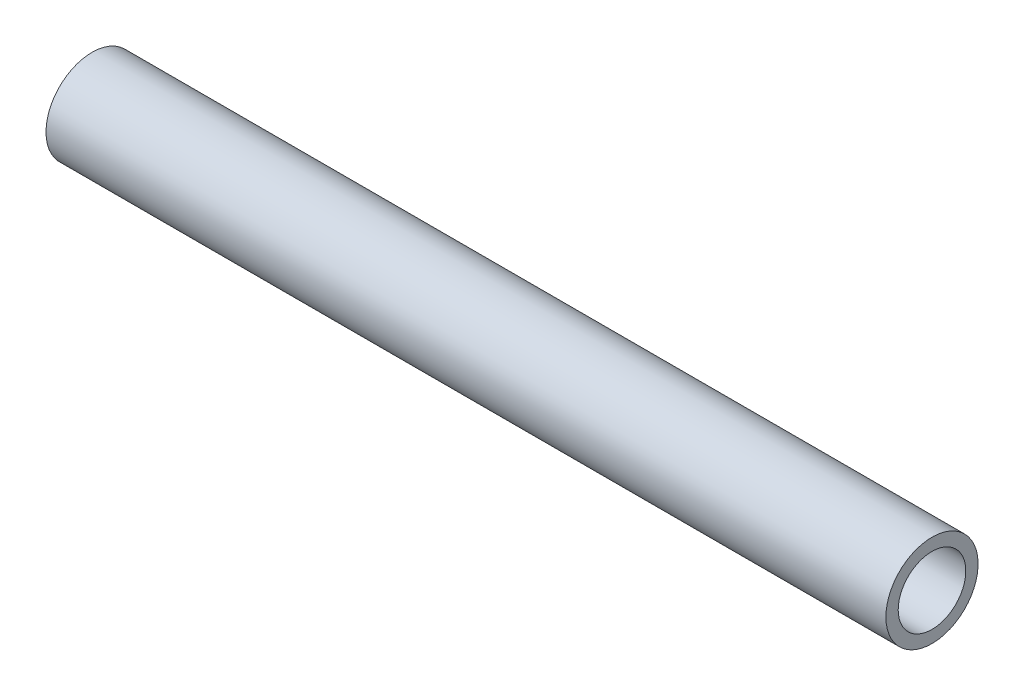
SolidWorks part; units mm, degrees
ref_plane "Front Plane" through (0, 0, 0) normal (0, 0, 1) x (1, 0, 0)
ref_plane "Top Plane" through (0, 0, 0) normal (0, 1, 0) x (1, 0, 0)
ref_plane "Right Plane" through (0, 0, 0) normal (1, 0, 0) x (0, 0, -1)
sketch "Axial profile (mm)" plane through (0, 0, 0) normal (0, 0, 1) x (1, 0, 0)
  line L0 (-110, 0) -> (75, 0) construction
  line L1 (118.7, 1.65) -> (159.7, 1.65)
  line L2 (159.7, 1.65) -> (159.7, 2.25)
  line L3 (159.7, 2.25) -> (118.7, 2.25)
  line L4 (118.7, 2.25) -> (118.7, 1.65)
revolve "Full revolution" add sketch "Axial profile (mm)" angle 360 about L0
